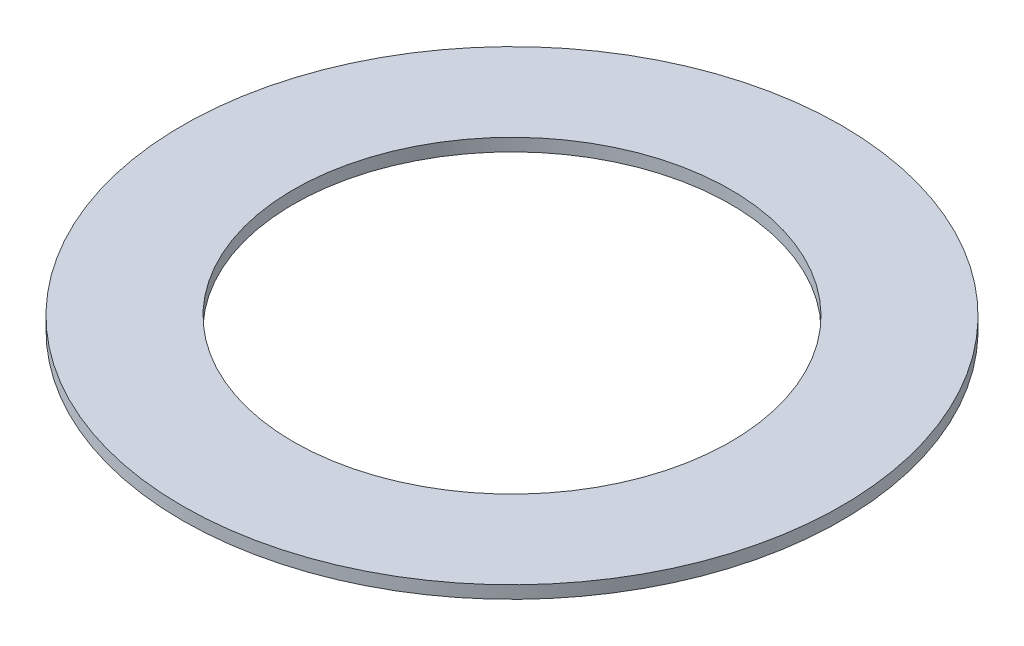
SolidWorks part; units mm, degrees
material "1060 Alloy"
ref_plane "Front Plane" through (0, 0, 0) normal (0, 0, 1) x (1, 0, 0)
ref_plane "Top Plane" through (0, 0, 0) normal (0, 1, 0) x (1, 0, 0)
ref_plane "Right Plane" through (0, 0, 0) normal (1, 0, 0) x (0, 0, -1)
sketch "Sketch1" plane through (0, 0, 0) normal (0, 1, 0) x (1, 0, 0)
  circle A0 centre (0, 0) radius 78.35
  circle A1 centre (0, 0) radius 49.55 construction
  circle A2 centre (0, 0) radius 51.95
  dimension "D1" = 156.7
  dimension "D2" = 99.1
  dimension "D3" = 2.4
extrude "Boss-Extrude1" add sketch "Sketch1" along normal blind 3
